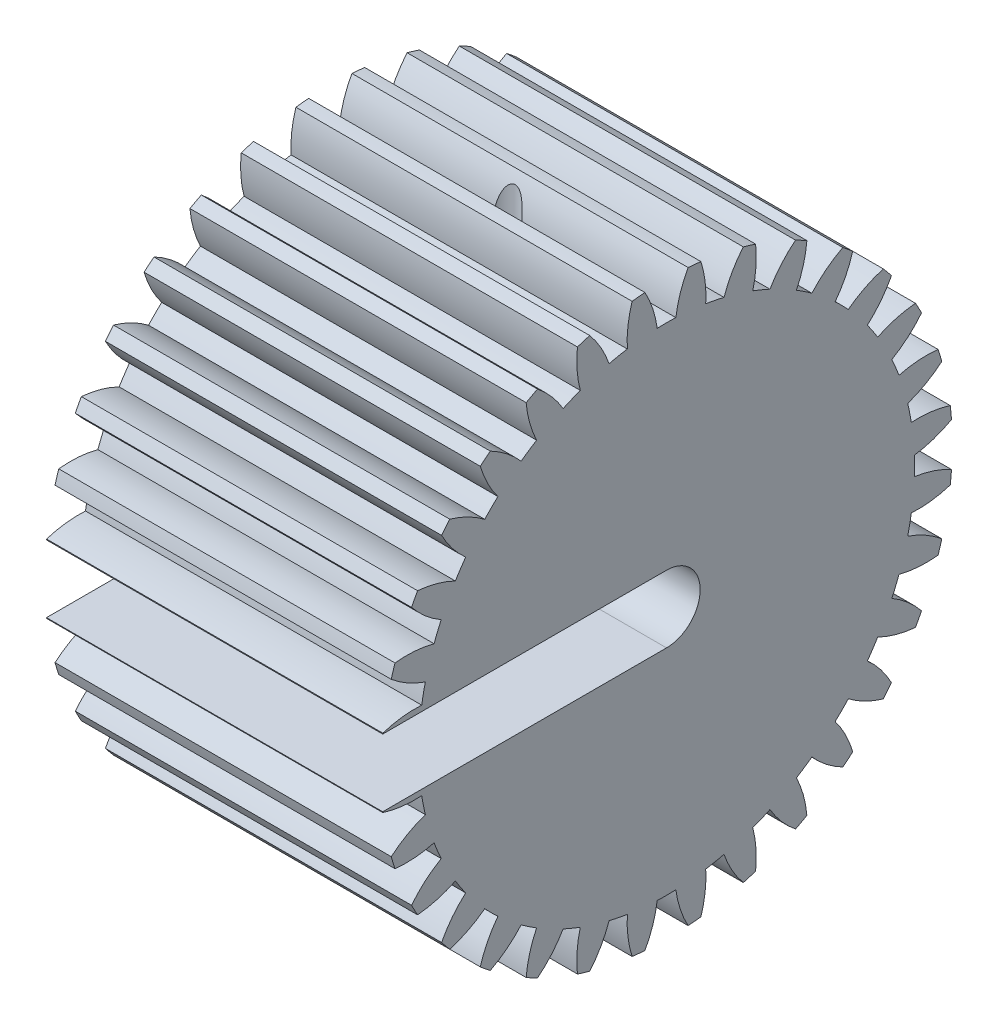
SolidWorks part; units mm, degrees
ref_plane "Plane1" through (0, 0, 0) normal (0, 0, 1) x (1, 0, 0)
ref_plane "Plane2" through (0, 0, 0) normal (0, 1, 0) x (1, 0, 0)
ref_plane "Plane3" through (0, 0, 0) normal (1, 0, 0) x (0, 0, -1)
other "Configuration Table"
sketch "HoldingSke" plane through (0, 0, 0) normal (0, 1, 0) x (1, 0, 0)
  line L0 (0, 0) -> (1.6961, -1.0598)
  line L1 (-15, 0) -> (100, 0) construction
  line L2 (0, 0) -> (-2.1039, 2.3779)
  line L3 (0, 0) -> (-11.863, 4.5341)
  line L4 (0, 0) -> (7.3237, 4.5764)
  line L5 (0, 0) -> (-46.8476, -17.4728)
  line L6 (0, 0) -> (-8.2896, -5.593)
  line L7 (-2.1039, 2.3779) -> (8.6586, 51.2059)
  line L8 (-76.2, 54.61) -> (-75.9, 54.61)
  line L9 (-67.7845, 28.3722) -> (-49.3413, 33.142)
  line L10 (-76.2, 71.12) -> (104.1128, 71.12)
  line L11 (0, 0) -> (-10, 0)
  line L12 (-76.2, 101.6) -> (-76.181, 101.6)
  line L13 (24.9733, 27.94) -> (52.9518, 28.4284)
  line L14 (24.9733, 27.94) -> (24.9743, 27.94)
  line L15 (24.9733, 27.94) -> (100.4006, 29.5858)
  line L16 (-63.627, -0.5) -> (-12.827, -0.5)
  circle A0 centre (0, 0) radius 1
  circle A1 centre (0, 0) radius 7.374
  circle A2 centre (0, 0) radius 37.5
  circle A3 centre (0, 0) radius 1
  dimension "MHD" = 14.748
  dimension "Hub_dia" = 75
  dimension "Bore" = 2
  dimension "MBD" = 2
  dimension "Num_teeth" = 32
  dimension "Pitch" = 2
  dimension "Overall_len" = 50
  dimension "Show_teeth" = 32
  dimension "Thickness" = 10
  dimension "OAL" = 50.0001
  dimension "T_dim" = 0.3
  dimension "Ap" = 14.5
  dimension "H" = 19.05
  dimension "Pitch_radius" = 180.3128
  dimension "Width" = 10
  dimension "Backlash" = 0.019
  dimension "Addendum_fac" = 1
  dimension "Dedendum_fac" = 1.25
  dimension "Clearance_fac" = 0.25
  dimension "Dedendum_add" = 0.001
  dimension "Module" = 0.5
sketch "BasProSke" plane through (0, 0, 0) normal (0, 1, 0) x (1, 0, 0)
  line L0 (-10, 0) -> (60, 0) construction
  line L1 (0, 0) -> (0, 8.5)
  line L2 (0, 0) -> (10, 0)
  line L3 (10, 0) -> (10, 8.5)
  line L4 (10, 8.5) -> (0, 8.5)
  dimension "Thickness" = 10
  dimension "Diameter" = 17
revolve "Base-Revolve" add sketch "BasProSke" angle 360 about L0
sketch "TooCutSke" plane through (0, 0, 0) normal (1, 0, 0) x (0, 0, -1)
  line L1 (0, 0) -> (0, 107) construction
  line L2 (0, 0) -> (-0.4258, 7.9887) construction
  line L3 (0, 0) -> (-1.5667, 15.9069) construction
  line L4 (-0.4258, 7.9887) -> (-0.7833, 7.9534) construction
  arc A0 (0.277, 7.3688) -> (-0.277, 7.3688) centre (0, 0) ccw
  arc A1 (0.6561, 8.5001) -> (-0.6561, 8.5001) centre (0, 0) ccw
  circle A2 centre (0, 0) radius 8 construction
  circle A3 centre (0, 0) radius 7.7452 construction
  arc A4 (-0.277, 7.3688) -> (-0.6561, 8.5001) centre (-3.4475, 6.9356) ccw
  arc A5 (0.6561, 8.5001) -> (0.277, 7.3688) centre (3.4475, 6.9356) ccw
  dimension "Root_dia" = 14.748
  dimension "Overcut_dia" = 17.0508
  dimension "Pitch_dia" = 16
  dimension "Base_dia" = 15.4904
  dimension "Flank_rad" = 3.2
  dimension "Half_ang" = 5.625
  dimension "Half_CT" = 0.3593
extrude "ToothCut" cut sketch "TooCutSke" along normal through all
fillet "Breaks" [suppressed] radius 0.01
fillet "RootFillets" [suppressed] radius 0.126
pattern_circular "TeethCuts" count 32 every 11.25 about axis through (-10, 0, 0) along (1, 0, 0) of "ToothCut", "RootFillets", "Breaks"
sketch "HubNeaOneSke" plane through (0, 0, 0) normal (-1, 0, 0) x (0, 0, 1)
  circle A0 centre (0, 0) radius 7.374
  dimension "Diameter" = 14.748
extrude "HubNearOne" [suppressed] add sketch "HubNeaOneSke" along normal blind 40.0001
sketch "HubNeaBotSke" plane through (0, 0, 0) normal (-1, 0, 0) x (0, 0, 1)
  circle A0 centre (0, 0) radius 7.374
  dimension "Diameter" = 14.748
extrude "HubNearBoth" [suppressed] add sketch "HubNeaBotSke" along normal blind 20
ref_plane "FarPln" through (10, 0, 0) normal (1, 0, 0) x (0, 0, -1)
sketch "HubFarSke" plane through (10, 0, 0) normal (1, 0, 0) x (0, 0, -1)
  circle A0 centre (0, 0) radius 7.374
  dimension "Diameter" = 14.748
extrude "HubFar" [suppressed] add sketch "HubFarSke" along normal blind 20
sketch "BorSke" plane through (0, 0, 0) normal (1, 0, 0) x (0, 0, -1)
  circle A0 centre (0, 0) radius 1
  dimension "Diameter" = 2
extrude "Bore" cut sketch "BorSke" along normal mid plane 100.0001
sketch "KeySke" plane through (0, 0, 0) normal (1, 0, 0) x (0, 0, -1)
  line L0 (-0.4, 0) -> (-0.4, 1.3)
  line L1 (-0.4, 1.3) -> (0.4, 1.3)
  line L2 (0.4, 1.3) -> (0.4, 0)
  line L3 (0, 0) -> (0, 34) construction
  line L4 (-0.4, 0) -> (0.4, 0)
  dimension "Offset" = 1.3
  dimension "Width" = 0.8
extrude "Keyway" [suppressed] cut sketch "KeySke" along normal mid plane 100.0001
pattern_circular "Keyway2" [suppressed] count 2 every 90 about axis through (-10, 0, 0) along (1, 0, 0)
sketch "Sketch1" plane through (10, 0, 0) normal (1, 0, 0) x (0, 0, -1)
  line L0 (0, 1) -> (-10, 1)
  line L1 (-10, 1) -> (-10, -1)
  line L2 (-10, -1) -> (0, -1)
  line L3 (0, -1) -> (0, 1)
  circle A0 centre (0, 0) radius 1 construction
  dimension "D1" = 10
  dimension "D2" = 2
extrude "Cut-Extrude1" cut sketch "Sketch1" against normal through all
sketch "Sketch2" plane through (0, 1, 0) normal (0, -1, 0) x (1, 0, 0)
  line L0 (0, 0) -> (10, 0) construction
  line L1 (0, 0.277) -> (0, -0.277) construction
  line L2 (10, -0.277) -> (10, 0.277) construction
  circle A0 centre (5, 0) radius 0.5
  dimension "D2" = 1
  dimension "D1" = 10
extrude "Cut-Extrude2" cut sketch "Sketch2" against normal through all both and the other way through all
equation "' \"Module@HoldingSke\" = 6.35"
equation "' \"Num_teeth@HoldingSke\" = 12"
equation "' \"Ap@HoldingSke\" =  20"
equation "' \"Ap@HoldingSke\" = 20"
equation "' \"Width@HoldingSke\" = 0.5 * 25.4"
equation "' \"Hub_dia@HoldingSke\"= 1 * 25.4"
equation "' \"Hub_dia@HoldingSke\" = 1 * 25.4"
equation "' \"Overall_len@HoldingSke\" = 1.0 * 25.4"
equation "' \"Bore@HoldingSke\" = 0.75 * 25.4"
equation "' \"T_dim@HoldingSke\" = 0.1 * 25.4"
equation "' \"Width@KeySke\" = 0.25 * 25.4"
equation "' \"Show_teeth@HoldingSke\" = 13"
equation "' \"Backlash@HoldingSke\" = 0.009 * 25.4"
equation "' \"Addendum_fac@HoldingSke\" = 1.0"
equation "' \"Dedendum_fac@HoldingSke\" = 1.25"
equation "' \"Dedendum_add@HoldingSke\" = 0.00005 * 25.4"
equation "' \"Clearance_fac@HoldingSke\" = 0.25"
equation "\"Pitch@HoldingSke\" = 1 / \"Module@HoldingSke\""
equation "\"Overcut_dia@TooCutSke\" = (\"Num_teeth@HoldingSke\" + 2 * \"Addendum_fac@HoldingSke\") / \"Pitch@HoldingSke\" + 0.002 * 25.4"
equation "\"Pitch_dia@TooCutSke\" = \"Num_teeth@HoldingSke\" / \"Pitch@HoldingSke\""
equation "\"Base_dia@TooCutSke\" = \"Num_teeth@HoldingSke\" / \"Pitch@HoldingSke\" * cos((\"Ap@HoldingSke\"  * 3.14159265 / 180))"
equation "\"Root_dia@TooCutSke\" = (\"Num_teeth@HoldingSke\" + 2) / \"Pitch@HoldingSke\" - 2 * (\"Addendum_fac@HoldingSke\" + \"Dedendum_fac@HoldingSke\") / \"Pitch@HoldingSke\" - \"Dedendum_add@HoldingSke\" * 2"
equation "\"Half_ang@TooCutSke\" = 180 / \"Num_teeth@HoldingSke\""
equation "\"Half_CT@TooCutSke\" = \"Num_teeth@HoldingSke\" / \"Pitch@HoldingSke\" * sin((3.14159265 / 2 / \"Num_teeth@HoldingSke\")) / 2 - 7 * \"Backlash@HoldingSke\" / 4"
equation "\"Flank_rad@TooCutSke\" = \"Num_teeth@HoldingSke\" / \"Pitch@HoldingSke\" / 5"
equation "\"Radius@RootFillets\" = \"Clearance_fac@HoldingSke\" / \"Pitch@HoldingSke\" + \"Dedendum_add@HoldingSke\""
equation "\"Break_rad@Breaks\" = 0.02 / \"Pitch@HoldingSke\""
equation "\"Thickness@HoldingSke\" = \"Width@HoldingSke\""
equation "\"OAL@HoldingSke\" = \"Thickness@HoldingSke\""
equation "\"MHD@HoldingSke\" = (\"Num_teeth@HoldingSke\" + 2) / \"Pitch@HoldingSke\" - 2 * (\"Addendum_fac@HoldingSke\" + \"Dedendum_fac@HoldingSke\")  / \"Pitch@HoldingSke\" - \"Dedendum_add@HoldingSke\" * 2"
equation "\"MBD@HoldingSke\" = (\"Num_teeth@HoldingSke\" + 2) / \"Pitch@HoldingSke\" - 2 * (\"Addendum_fac@HoldingSke\" + \"Dedendum_fac@HoldingSke\")  / \"Pitch@HoldingSke\" - \"Dedendum_add@HoldingSke\" * 2 - 0.002 * 25.4"
equation "\"MHD@HoldingSke\" = ((sgn( \"MHD@HoldingSke\" - \"Hub_dia@HoldingSke\" )-1)*( \"MHD@HoldingSke\" - \"Hub_dia@HoldingSke\" ))/-2+ \"Hub_dia@HoldingSke\""
equation "\"MBD@HoldingSke\" = ((sgn( \"MBD@HoldingSke\" - \"Bore@HoldingSke\" )-1)*( \"MBD@HoldingSke\" - \"Bore@HoldingSke\" ))/-2+ \"Bore@HoldingSke\""
equation "\"OAL@HoldingSke\" = ((sgn( \"OAL@HoldingSke\" - \"Overall_len@HoldingSke\" )+1)*( \"OAL@HoldingSke\" - \"Overall_len@HoldingSke\" ))/2 + \"Overall_len@HoldingSke\" + 0.000002 * 25.4"
equation "\"Num_teeth@TeethCuts\" = int( \"Show_teeth@HoldingSke\" ) + 1"
equation "\"Num_teeth@TeethCuts\" = ((sgn( \"Num_teeth@TeethCuts\" - \"Num_teeth@HoldingSke\" )-1)*( \"Num_teeth@TeethCuts\" - \"Num_teeth@HoldingSke\" ))/-2+ \"Num_teeth@HoldingSke\""
equation "\"Num_teeth@TeethCuts\" = ((sgn( \"Num_teeth@TeethCuts\" - 2.0)+1)*( \"Num_teeth@TeethCuts\" - 2.0))/2 +2.0"
equation "\"Angle@TeethCuts\" = 360.0 / \"Num_teeth@HoldingSke\""
equation "\"Diameter@BasProSke\" = (\"Num_teeth@HoldingSke\" + 2 * \"Addendum_fac@HoldingSke\") / \"Pitch@HoldingSke\""
equation "\"Thickness@BasProSke\"  = \"Thickness@HoldingSke\""
equation "' \"Fillet_rad@BasProSke\" =  \"Thickness@HoldingSke\" * 0.05"
equation "' \"Fillet_rad@BasProSke\" = \"Thickness@HoldingSke\" * 0.05"
equation "\"MHD@HoldingSke\" = ((sgn( \"MHD@HoldingSke\" - \"Root_dia@TooCutSke\" )-1)*( \"MHD@HoldingSke\" - \"Root_dia@TooCutSke\" ))/-2+ \"Root_dia@TooCutSke\""
equation "\"Diameter@HubNeaOneSke\" = \"MHD@HoldingSke\""
equation "\"Length@HubNearOne\" = \"OAL@HoldingSke\" - \"Thickness@BasProSke\""
equation "\"Diameter@HubNeaBotSke\" = \"MHD@HoldingSke\""
equation "\"Length@HubNearBoth\" = ( \"OAL@HoldingSke\" - \"Thickness@BasProSke\" ) / 2.0"
equation "\"Thickness@FarPln\" = \"Thickness@BasProSke\""
equation "\"Diameter@HubFarSke\" = \"MHD@HoldingSke\""
equation "\"Length@HubFar\" = ( \"OAL@HoldingSke\" - \"Thickness@BasProSke\" ) / 2.0"
equation "\"Diameter@BorSke\" = \"MBD@HoldingSke\""
equation "\"D1@Bore\" = \"OAL@HoldingSke\" * 2.0"
equation "\"D1@Keyway\" = \"OAL@HoldingSke\" * 2.0"
equation "\"Offset@KeySke\" = \"T_dim@HoldingSke\" + \"MBD@HoldingSke\" / 2.0"
